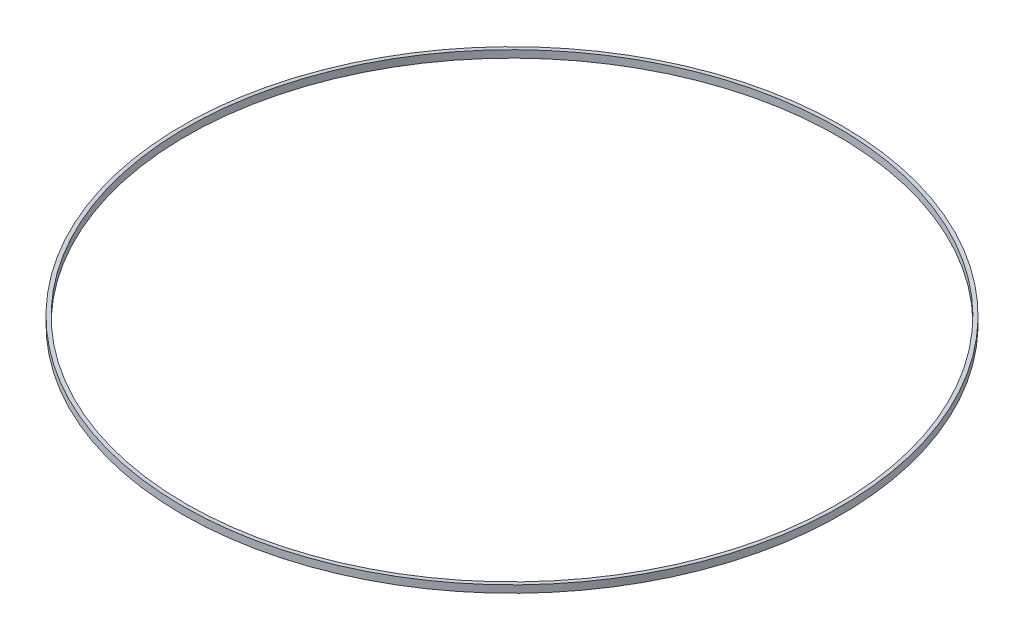
SolidWorks part; units mm, degrees
material "Rubber"
ref_plane "Front Plane" through (0, 0, 0) normal (0, 0, 1) x (1, 0, 0)
ref_plane "Top Plane" through (0, 0, 0) normal (0, 1, 0) x (1, 0, 0)
ref_plane "Right Plane" through (0, 0, 0) normal (1, 0, 0) x (0, 0, -1)
sketch "Sketch1" plane through (0, 0, 0) normal (0, 1, 0) x (1, 0, 0)
  circle A0 centre (0, 0) radius 45
  circle A1 centre (0, 0) radius 44.5
  dimension "D1" = 90
  dimension "D2" = 89
extrude "Boss-Extrude1" add sketch "Sketch1" along normal blind 1
